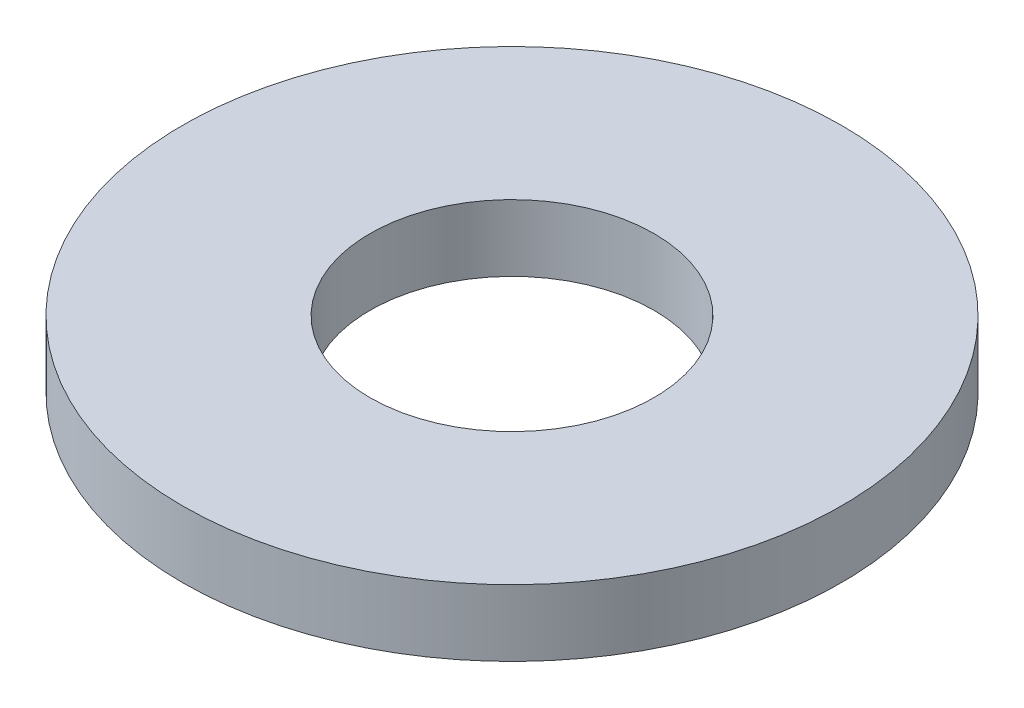
SolidWorks part; units mm, degrees
ref_plane "Front Plane" through (0, 0, 0) normal (0, 0, 1) x (1, 0, 0)
ref_plane "Top Plane" through (0, 0, 0) normal (0, 1, 0) x (1, 0, 0)
ref_plane "Right Plane" through (0, 0, 0) normal (1, 0, 0) x (0, 0, -1)
sketch "Sketch1" plane through (0, 0, 0) normal (0, 1, 0) x (1, 0, 0)
  circle A0 centre (0, 0) radius 2.7686
  dimension "OD" = 5.5372
extrude "Boss-Extrude1" add sketch "Sketch1" along normal blind 0.5588
sketch "Sketch5" plane through (0, 0.5588, 0) normal (0, 1, 0) x (-1, 0, 0)
  circle A0 centre (0, 0) radius 1.1938
  dimension "ID" = 2.3876
extrude "Cut-Extrude1" cut sketch "Sketch5" against normal through all
